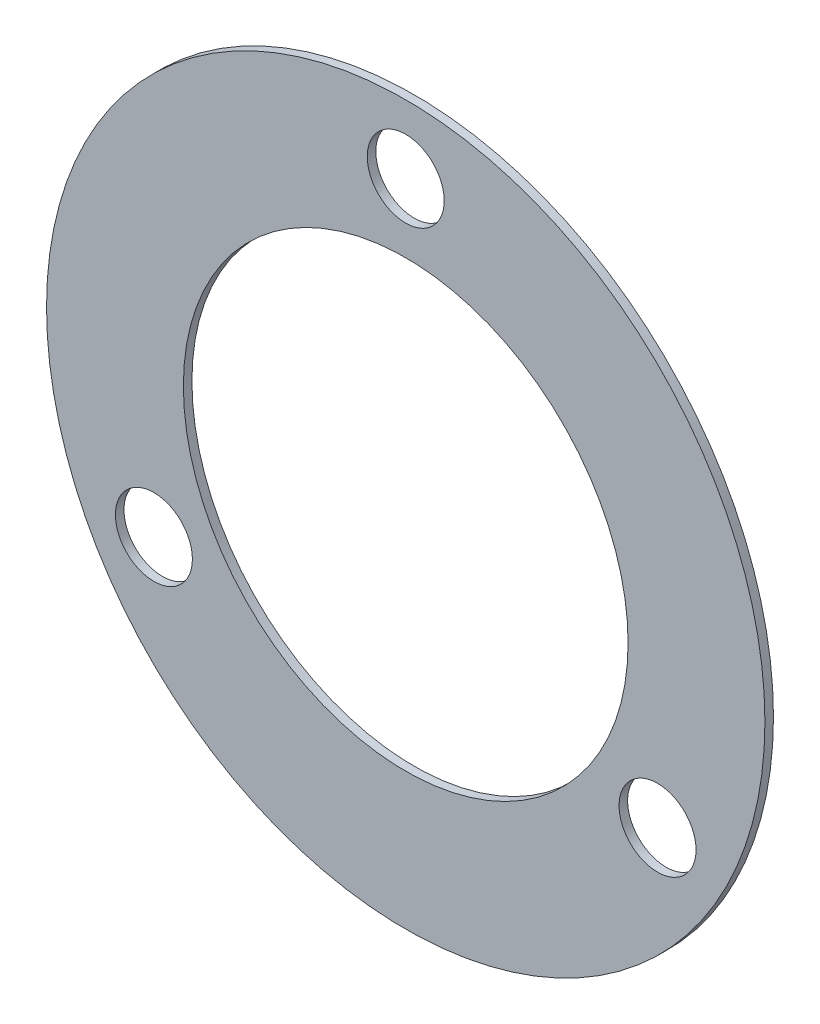
SolidWorks part; units mm, degrees
ref_plane "Piano frontale" through (0, 0, 0) normal (0, 0, 1) x (1, 0, 0)
ref_plane "Piano superiore" through (0, 0, 0) normal (0, 1, 0) x (1, 0, 0)
ref_plane "Piano destro" through (0, 0, 0) normal (1, 0, 0) x (0, 0, -1)
sketch "Schizzo1" plane through (0, 0, 0) normal (0, 0, 1) x (1, 0, 0)
  line L0 (0, 0) -> (0, 52.6194) construction
  circle A0 centre (0, 0) radius 26
  circle A1 centre (0, 0) radius 42
  circle A2 centre (0, 34) radius 4.5
  circle A3 centre (29.4449, -17) radius 4.5
  circle A4 centre (-29.4449, -17) radius 4.5
  point P14 (0, 0)
  dimension "D1" = 52
  dimension "D2" = 84
  dimension "D3" = 9
  dimension "D4" = 3
  dimension "34" = 34
extrude "Estrusione-Estrusione1" add sketch "Schizzo1" along normal blind 1
